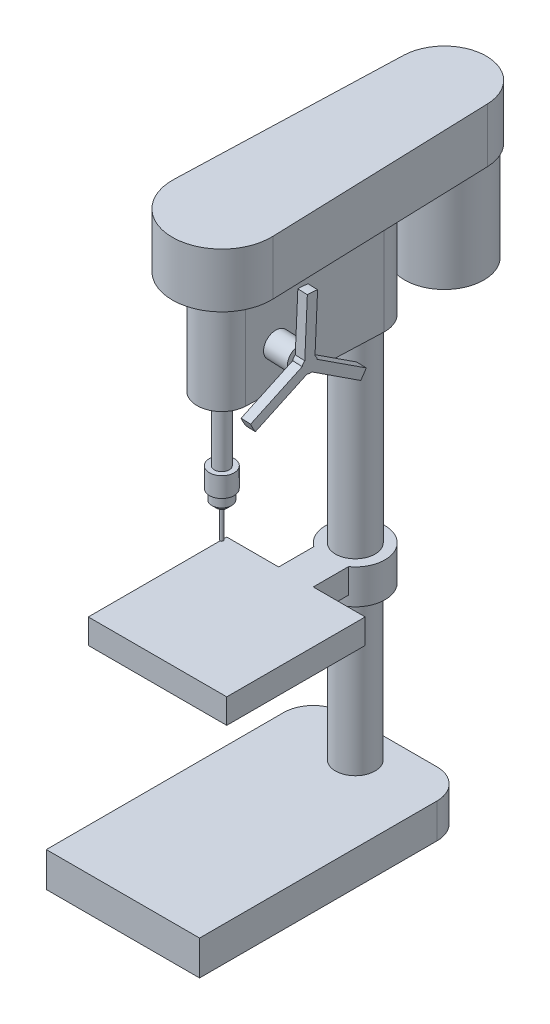
SolidWorks part; units mm, degrees
ref_plane "正面" through (0, 0, 0) normal (0, 0, 1) x (1, 0, 0)
ref_plane "平面" through (0, 0, 0) normal (0, 1, 0) x (1, 0, 0)
ref_plane "右側面" through (0, 0, 0) normal (1, 0, 0) x (0, 0, -1)
sketch "ｽｹｯﾁ1" plane through (0, 0, 0) normal (0, 1, 0) x (1, 0, 0)
  line L1 (0, 0) -> (310, 0)
  line L2 (0, 0) -> (0, 540)
  line L3 (0, 540) -> (310, 540)
  line L4 (310, 0) -> (310, 540)
  dimension "D1" = 310
  dimension "D2" = 540
extrude "ﾎﾞｽ - 押し出し1" add sketch "ｽｹｯﾁ1" along normal blind 70
fillet "ﾌｨﾚｯﾄ1" radius 60 2 edges at (0, 35, -540) (310, 35, -540)
sketch "ｽｹｯﾁ2" plane through (0, 70, 0) normal (0, 1, 0) x (1, 0, 0)
  line L0 (310, 0) -> (310, 480) construction
  line L1 (250, 540) -> (60, 540) construction
  circle A0 centre (155, 470) radius 40
  dimension "D1" = 80
  dimension "D2" = 155
  dimension "D3" = 70
extrude "ﾎﾞｽ - 押し出し2" add sketch "ｽｹｯﾁ2" along normal blind 310
sketch "ｽｹｯﾁ3" plane through (0, 380, 0) normal (0, 1, 0) x (1, 0, 0)
  circle A0 centre (155, 470) radius 60
  dimension "D1" = 120
extrude "ﾎﾞｽ - 押し出し3" add sketch "ｽｹｯﾁ3" along normal blind 20
sketch "ｽｹｯﾁ4" plane through (0, 400, 0) normal (0, 1, 0) x (1, 0, 0)
  line L0 (190, 350) -> (295, 350)
  line L1 (15, 70) -> (295, 70)
  line L2 (15, 70) -> (15, 350)
  line L3 (15, 350) -> (120, 350)
  line L4 (295, 70) -> (295, 350)
  line L6 (120, 421.266) -> (120, 350)
  line L8 (190, 421.266) -> (190, 350)
  arc A0 (190, 421.266) -> (120, 421.266) centre (155, 470) ccw
  dimension "D1" = 120
  dimension "D2" = 280
  dimension "D3" = 280
  dimension "D4" = 140
  dimension "D5" = 35
  dimension "D6" = 120
  dimension "D8" = 35
extrude "ﾎﾞｽ - 押し出し4" add sketch "ｽｹｯﾁ4" along normal blind 50
sketch "ｽｹｯﾁ5" plane through (0, 450, 0) normal (0, 1, 0) x (1, 0, 0)
  circle A0 centre (155, 470) radius 40
  dimension "D1" = 80
extrude "ﾎﾞｽ - 押し出し5" add sketch "ｽｹｯﾁ5" along normal blind 400
sketch "ｽｹｯﾁ8" plane through (0, 850, 0) normal (0, 1, 0) x (1, 0, 0)
  line L0 (95.0412, 467.7778) -> (105.0343, 198.1481)
  line L1 (214.9588, 467.7778) -> (204.9657, 198.1481)
  arc A0 (214.9588, 467.7778) -> (95.0412, 467.7778) centre (155, 470) ccw
  circle A1 centre (155, 470) radius 40 construction
  arc A2 (105.0343, 198.1481) -> (204.9657, 198.1481) centre (155, 200) ccw
  dimension "D1" = 120
  dimension "100" = 100
  dimension "D3" = 270
extrude "ﾎﾞｽ - 押し出し6" add sketch "ｽｹｯﾁ8" along normal blind 210
sketch "ｽｹｯﾁ9" plane through (0, 1060, 0) normal (0, 1, 0) x (1, 0, 0)
  line L0 (55.0556, 203.3333) -> (70.0472, 652.8333)
  line L1 (239.9528, 652.8333) -> (254.9444, 203.3333)
  arc A0 (239.9528, 652.8333) -> (70.0472, 652.8333) centre (155, 650) ccw
  arc A1 (55.0556, 203.3333) -> (254.9444, 203.3333) centre (155, 200) ccw
  arc A3 (105.0343, 198.1481) -> (204.9657, 198.1481) centre (155, 200) ccw construction
  dimension "D1" = 170
  dimension "D2" = 200
  dimension "D3" = 450
extrude "ﾎﾞｽ - 押し出し7" add sketch "ｽｹｯﾁ9" along normal blind 110
sketch "ｽｹｯﾁ10" plane through (0, 1060, 0) normal (0, -1, 0) x (-1, 0, 0)
  circle A0 centre (-155, 650) radius 80
  arc A1 (-70.0472, 652.8333) -> (-239.9528, 652.8333) centre (-155, 650) ccw construction
  dimension "D1" = 160
extrude "ﾎﾞｽ - 押し出し8" add sketch "ｽｹｯﾁ10" along normal blind 200
sketch "ｽｹｯﾁ11" plane through (0, 850, 0) normal (0, -1, 0) x (-1, 0, 0)
  circle A0 centre (-155, 200) radius 15
  arc A1 (-204.9657, 198.1481) -> (-105.0343, 198.1481) centre (-155, 200) ccw construction
  dimension "D1" = 30
extrude "ﾎﾞｽ - 押し出し9" add sketch "ｽｹｯﾁ11" along normal blind 130
sketch "ｽｹｯﾁ12" plane through (0, 720, 0) normal (0, -1, 0) x (-1, 0, 0)
  circle A0 centre (-155, 200) radius 25
  circle A1 centre (-155, 200) radius 15 construction
  dimension "D1" = 50
extrude "ﾎﾞｽ - 押し出し10" add sketch "ｽｹｯﾁ12" along normal blind 40
sketch "ｽｹｯﾁ13" plane through (0, 680, 0) normal (0, -1, 0) x (-1, 0, 0)
  circle A0 centre (-155, 200) radius 20
  circle A1 centre (-155, 200) radius 25 construction
  dimension "D1" = 40
extrude "ﾎﾞｽ - 押し出し11" add sketch "ｽｹｯﾁ13" along normal blind 30
chamfer "面取り1" distance 10 angle 45 1 edges at (155, 650, -220)
sketch "ｽｹｯﾁ14" plane through (0, 650, 0) normal (0, -1, 0) x (-1, 0, 0)
  circle A0 centre (-155, 200) radius 3.5
  circle A1 centre (-155, 200) radius 10 construction
  dimension "D1" = 7
extrude "ﾎﾞｽ - 押し出し12" add sketch "ｽｹｯﾁ14" along normal blind 60
sketch "ｽｹｯﾁ15" plane through (197.3507, 0, 7.3143) normal (0.9993, 0, 0.037) x (0.037, 0, -0.9993)
  line L0 (205.6035, 850) -> (475.4183, 850) construction
  line L1 (205.6035, 1060) -> (205.6035, 850) construction
  circle A0 centre (265.6035, 930) radius 25
  dimension "D1" = 50
  dimension "D2" = 80
  dimension "D3" = 60
extrude "ﾎﾞｽ - 押し出し13" add sketch "ｽｹｯﾁ15" along normal blind 50
sketch "ｽｹｯﾁ16" plane through (247.3164, 0, 9.1662) normal (0.9993, 0, 0.037) x (0.037, 0, -0.9993)
  circle A0 centre (265.6035, 930) radius 125
  circle A1 centre (265.6035, 930) radius 25 construction
  dimension "D1" = 250
extrude "ﾎﾞｽ - 押し出し14" add sketch "ｽｹｯﾁ16" along normal blind 20
sketch "ｽｹｯﾁ17" plane through (267.3027, 0, 9.9069) normal (0.9993, 0, 0.037) x (0.037, 0, -0.9993)
  line L0 (265.6035, 930) -> (313.5013, 899.4343) construction
  line L1 (265.6035, 930) -> (207.6336, 899.879) construction
  line L2 (265.6035, 930) -> (268.4104, 993.1809) construction
  line L3 (251.0718, 933.7187) -> (150.4279, 881.4244)
  line L5 (159.6494, 863.6772) -> (260.2932, 915.9714)
  line L6 (269.6489, 915.5558) -> (365.259, 854.5428)
  line L7 (280.4078, 932.4154) -> (376.0179, 871.4024)
  line L8 (276.0899, 940.7255) -> (281.1236, 1054.0328)
  line L9 (256.1096, 941.6131) -> (261.1433, 1054.9204)
  circle A0 centre (265.6035, 930) radius 125 construction
  arc A1 (260.2932, 915.9714) -> (269.6489, 915.5558) centre (265.6035, 930) ccw
  circle A2 centre (265.6035, 930) radius 125
  arc A3 (256.1096, 941.6131) -> (251.0718, 933.7187) centre (265.6035, 930) ccw
  arc A4 (280.4078, 932.4154) -> (276.0899, 940.7255) centre (265.6035, 930) ccw
  circle M1 centre (265.6035, 930) radius 125
  dimension "D3" = 30
  dimension "D10" = 250
  dimension "D1" = 120
  dimension "D2" = 120
  dimension "D4" = 20
  dimension "D5" = 20
  dimension "D6" = 10
  dimension "D7" = 10
  dimension "D8" = 20
  dimension "D9" = 10
extrude "ｶｯﾄ - 押し出し1" cut sketch "ｽｹｯﾁ17" against normal blind 20 contours A3 L9 L3 M1 | A4 L7 L8 M1 | A1 L5 L6 M1
